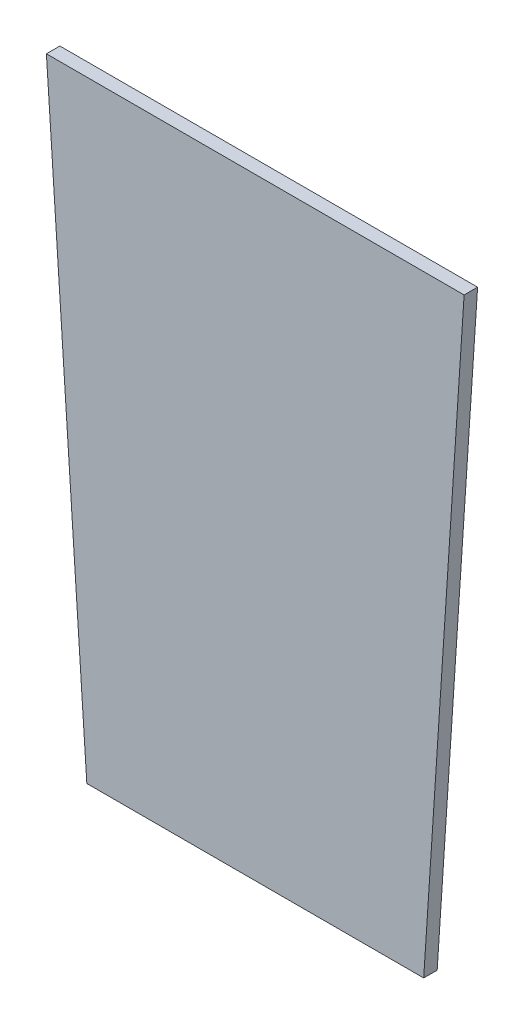
SolidWorks part; units mm, degrees
ref_plane "Płaszczyzna przednia" through (0, 0, 0) normal (0, 0, 1) x (1, 0, 0)
ref_plane "Płaszczyzna górna" through (0, 0, 0) normal (0, 1, 0) x (1, 0, 0)
ref_plane "Płaszczyzna prawa" through (0, 0, 0) normal (1, 0, 0) x (0, 0, -1)
sketch "Szkic1" plane through (0, 0, 0) normal (0, 0, 1) x (1, 0, 0)
  line L0 (-155, 227.005) -> (155, 227.005)
  line L1 (155, 227.005) -> (125, -227.005)
  line L2 (125, -227.005) -> (-125, -227.005)
  line L3 (-125, -227.005) -> (-155, 227.005)
  point P2 (0, 227.005)
  point P5 (0, -227.005)
  point P7 (-140, 0)
  dimension "D1" = 310
  dimension "D2" = 250
  dimension "D3" = 455
extrude "Dodanie-wyciągnięcie1" add sketch "Szkic1" along normal blind 10
